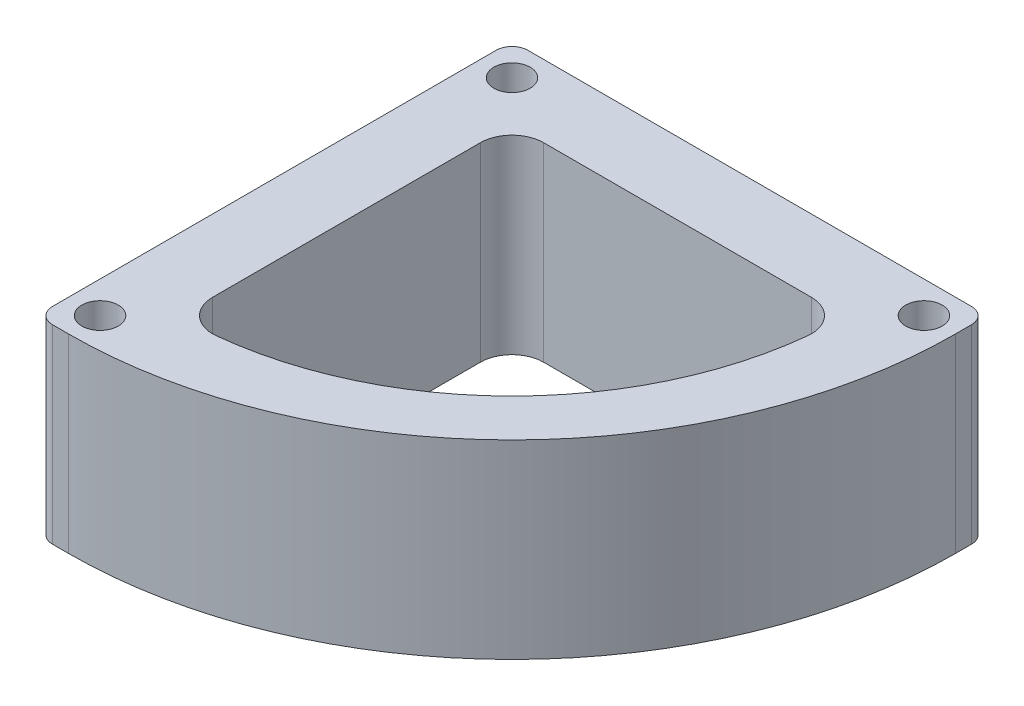
SolidWorks part; units mm, degrees
material "ABS"
ref_plane "前视基准面" through (0, 0, 0) normal (0, 0, 1) x (1, 0, 0)
ref_plane "上视基准面" through (0, 0, 0) normal (0, 1, 0) x (1, 0, 0)
ref_plane "右视基准面" through (0, 0, 0) normal (1, 0, 0) x (0, 0, -1)
sketch "草图1" plane through (0, 0, 0) normal (0, 1, 0) x (1, 0, 0)
  line L1 (-15, 15) -> (15, 15)
  line L2 (-15, 15) -> (-15, -15)
  line L3 (-15, -15) -> (15, -15)
  line L4 (15, 15) -> (15, -15)
  line L5 (0, -15) -> (0, 15) construction
  line L6 (-15, 0) -> (15, 0) construction
  circle A0 centre (13, 13) radius 1.15
  circle A1 centre (13, -13) radius 1.15
  circle A2 centre (-13, -13) radius 1.15
  circle A3 centre (-13, 13) radius 1.15
  point P0 (0, 0)
  dimension "D1" = 26
  dimension "D2" = 26
  dimension "D3" = 2.3
  dimension "D4" = 30
  dimension "D5" = 30
extrude "凸台-拉伸1" add sketch "草图1" along normal blind 12
fillet "圆角1" radius 28 1 edges at (15, 6, 15)
fillet "圆角2" radius 1 3 edges at (-15, 6, -15) (15, 6, -15) (-15, 6, 15)
sketch "草图2" plane through (0, 0, 0) normal (0, 1, 0) x (1, 0, 0)
  line L0 (-13, 13) -> (0, 0) construction
  line L4 (8.4472, 10.4472) -> (-8.4472, 10.4472)
  line L5 (-10.4472, -8.4472) -> (-10.4472, 8.4472)
  line L6 (0, 10.4472) -> (0, -10.5) construction
  line L7 (10.5, 0) -> (-10.4472, 0) construction
  arc A0 (10.4361, 8.2367) -> (-8.2367, -10.4361) centre (-10.4472, 10.4472) cw
  arc A1 (-8.4472, 10.4472) -> (-10.4472, 8.4472) centre (-8.4472, 8.4472) ccw
  arc A2 (-8.2367, -10.4361) -> (-10.4472, -8.4472) centre (-8.4472, -8.4472) cw
  arc A3 (10.4361, 8.2367) -> (8.4472, 10.4472) centre (8.4472, 8.4472) ccw
  point P7 (-10.4472, 10.4472)
  point P13 (10.5528, 10.4472)
  dimension "D2" = 21
  dimension "D3" = 2
  dimension "D1" = 21
extrude "切除-拉伸3" cut sketch "草图2" along normal blind 22
sketch "草图4" plane through (-15, 0, 0) normal (-1, 0, 0) x (0, 0, 1)
  line L0 (-15, 0) -> (-15, 12) construction
  line L1 (-14, 0) -> (14, 0) construction
  line L2 (-7.6307, 12) -> (11.6307, 12)
  line L3 (-14, 12) -> (14, 12) construction
  arc A0 (-7.6307, 12) -> (11.6307, 12) centre (2, 23.5) ccw
  arc A1 (11.6307, 12) -> (-7.6307, 12) centre (2, 23.5) ccw construction
  dimension "D1" = 17
  dimension "D2" = 23.5
  dimension "D3" = 30
